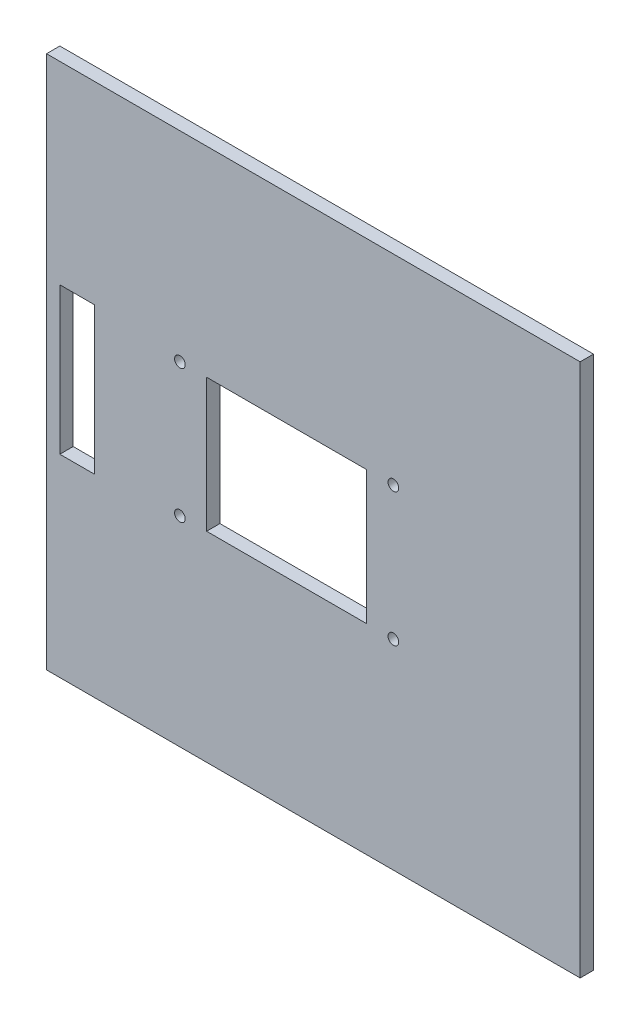
SolidWorks part; units mm, degrees
ref_plane "Plan de face" through (0, 0, 0) normal (0, 0, 1) x (1, 0, 0)
ref_plane "Plan de dessus" through (0, 0, 0) normal (0, 1, 0) x (1, 0, 0)
ref_plane "Plan de droite" through (0, 0, 0) normal (1, 0, 0) x (0, 0, -1)
sketch "Esquisse1" plane through (0, 0, 0) normal (0, 0, 1) x (1, 0, 0)
  line L1 (0, 0) -> (200, 0)
  line L2 (0, 0) -> (0, 200)
  line L3 (0, 200) -> (200, 200)
  line L4 (200, 0) -> (200, 200)
  dimension "D1" = 200
  dimension "D2" = 200
extrude "Boss.-Extru.1" add sketch "Esquisse1" along normal blind 5
sketch "Esquisse2" plane through (0, 0, 5) normal (0, 0, 1) x (1, 0, 0)
  line L0 (50, 125) -> (130, 125) construction
  line L1 (130, 125) -> (130, 75) construction
  line L2 (130, 75) -> (50, 75) construction
  line L3 (50, 75) -> (50, 125) construction
  line L4 (0, 200) -> (0, 0) construction
  line L5 (0, 100) -> (200, 100) construction
  line L6 (200, 0) -> (200, 200) construction
  circle A0 centre (50, 125) radius 2
  circle A1 centre (50, 75) radius 2
  circle A2 centre (130, 125) radius 2
  circle A3 centre (130, 75) radius 2
  point P14 (50, 100)
  dimension "D3" = 4
  dimension "D4" = 4
  dimension "D5" = 4
  dimension "D6" = 4
  dimension "D1" = 80
  dimension "D2" = 50
  dimension "D7" = 50
extrude "Enlèv. mat.-Extru.1" cut sketch "Esquisse2" against normal blind 10
sketch "Esquisse3" plane through (0, 0, 5) normal (0, 0, 1) x (1, 0, 0)
  line L0 (0, 200) -> (0, 0) construction
  line L1 (5, 127.5) -> (18, 127.5)
  line L2 (5, 127.5) -> (5, 72.5)
  line L3 (5, 72.5) -> (18, 72.5)
  line L4 (18, 127.5) -> (18, 72.5)
  line L5 (0, 100) -> (52.0907, 100) construction
  point P8 (5, 100)
  dimension "D1" = 5
  dimension "D2" = 55
  dimension "D3" = 13
extrude "Enlèv. mat.-Extru.2" cut sketch "Esquisse3" against normal blind 10
sketch "Esquisse4" plane through (0, 0, 5) normal (0, 0, 1) x (1, 0, 0)
  line L0 (50, 125) -> (130, 125) construction
  line L1 (130, 125) -> (130, 75) construction
  line L2 (130, 75) -> (50, 75) construction
  line L3 (50, 75) -> (50, 125) construction
  line L4 (50, 100) -> (130, 100) construction
  line L5 (60, 125) -> (120, 125)
  line L6 (60, 125) -> (60, 75)
  line L7 (60, 75) -> (120, 75)
  line L8 (120, 125) -> (120, 75)
  line L9 (50, 64.3094) -> (60, 64.3094) construction
  line L10 (120, 64.3094) -> (130, 64.3094) construction
  point P14 (60, 100)
  dimension "D1" = 60
extrude "Enlèv. mat.-Extru.3" cut sketch "Esquisse4" against normal blind 12
